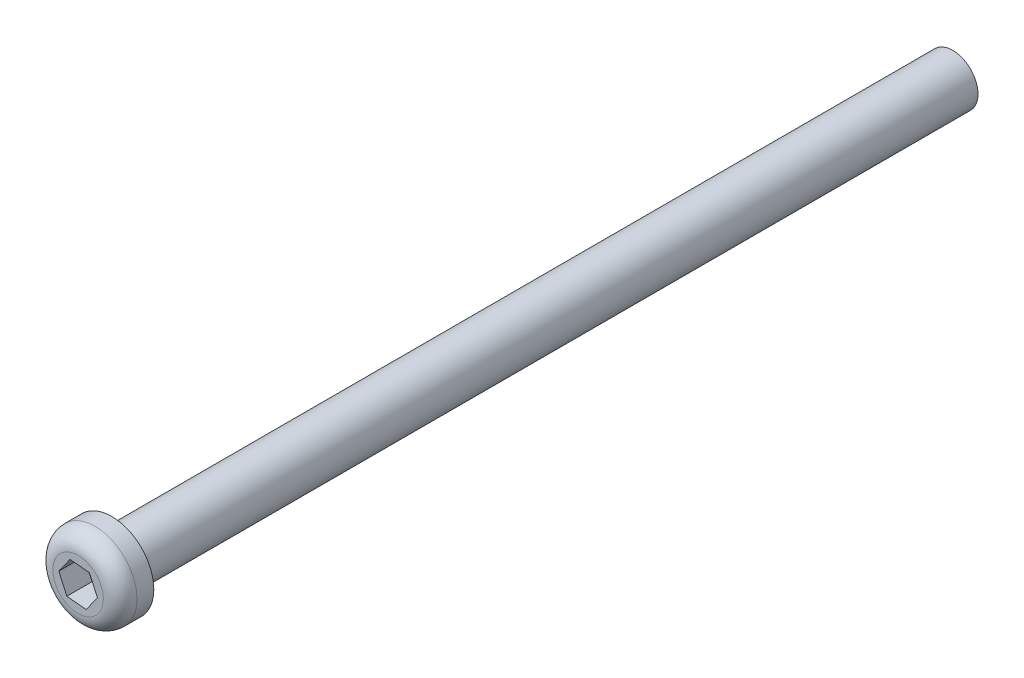
SolidWorks part; units mm, degrees
ref_plane "前视基准面" through (0, 0, 0) normal (0, 0, 1) x (1, 0, 0)
ref_plane "上视基准面" through (0, 0, 0) normal (0, 1, 0) x (1, 0, 0)
ref_plane "右视基准面" through (0, 0, 0) normal (1, 0, 0) x (0, 0, -1)
sketch "草图1" plane through (0, 0, 0) normal (0, 0, 1) x (1, 0, 0)
  circle A0 centre (0, 0) radius 1.5
  dimension "D1" = 3
extrude "凸台-拉伸1" add sketch "草图1" along normal blind 50
sketch "草图2" plane through (0, 0, 50) normal (0, 0, 1) x (1, 0, 0)
  circle A0 centre (0, 0) radius 2.5
  dimension "D1" = 5
extrude "凸台-拉伸2" add sketch "草图2" along normal blind 2
sketch "草图3" plane through (0, 0, 52) normal (0, 0, 1) x (1, 0, 0)
  line L1 (1.1496, -0.108) -> (0.6683, 0.9416)
  line L2 (0.6683, 0.9416) -> (-0.4813, 1.0496)
  line L3 (-0.4813, 1.0496) -> (-1.1496, 0.108)
  line L4 (-1.1496, 0.108) -> (-0.6683, -0.9416)
  line L5 (-0.6683, -0.9416) -> (0.4813, -1.0496)
  line L6 (0.4813, -1.0496) -> (1.1496, -0.108)
  circle A0 centre (0, 0) radius 1 construction
  dimension "D1" = 2
extrude "切除-拉伸1" cut sketch "草图3" against normal blind 1.5
fillet "圆角2" radius 1 1 edges at (2.5, 0, 52)
